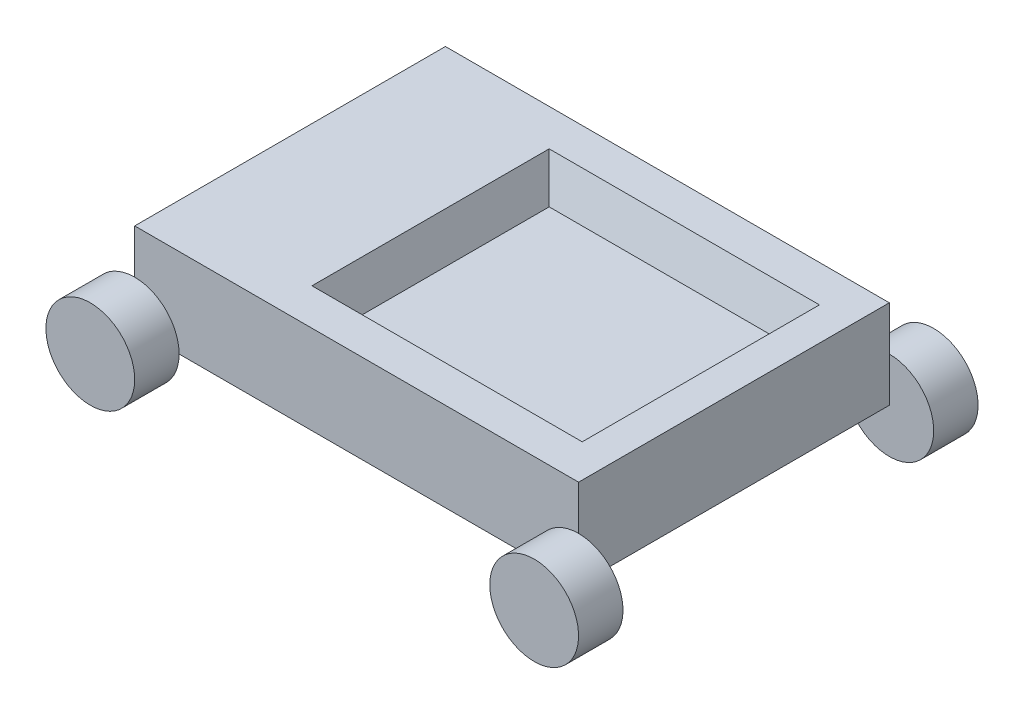
SolidWorks part; units mm, degrees
ref_plane "前视基准面" through (0, 0, 0) normal (0, 0, 1) x (1, 0, 0)
ref_plane "上视基准面" through (0, 0, 0) normal (0, 1, 0) x (1, 0, 0)
ref_plane "右视基准面" through (0, 0, 0) normal (1, 0, 0) x (0, 0, -1)
sketch "草图1" plane through (0, 0, 0) normal (0, 1, 0) x (1, 0, 0)
  line L1 (500, -350) -> (-500, -350)
  line L2 (500, -350) -> (500, 350)
  line L3 (500, 350) -> (-500, 350)
  line L4 (-500, -350) -> (-500, 350)
  line L5 (500, -350) -> (-500, 350) construction
  line L6 (500, 350) -> (-500, -350) construction
  point P0 (0, 0)
  dimension "D1" = 1000
  dimension "D2" = 700
extrude "凸台-拉伸1" add sketch "草图1" along normal blind 200
sketch "草图2" plane through (0, 0, 350) normal (0, 0, 1) x (1, 0, 0)
  circle A0 centre (-500, 0) radius 100
  dimension "D1" = 200
extrude "凸台-拉伸2" add sketch "草图2" along normal blind 100
mirror "镜向1" about plane through (0, 0, 0) normal (1, 0, 0) of "凸台-拉伸2"
mirror "镜向2" about plane through (0, 0, 0) normal (0, 0, 1) of "镜向1", "凸台-拉伸2"
sketch "草图3" plane through (0, 200, 0) normal (0, 1, 0) x (1, 0, 0)
  line L5 (-183.4427, -267.1882) -> (425.3743, -267.1882)
  line L6 (-183.4427, -267.1882) -> (-183.4427, 267.1882)
  line L7 (-183.4427, 267.1882) -> (425.3743, 267.1882)
  line L8 (425.3743, -267.1882) -> (425.3743, 267.1882)
  line L9 (-183.4427, -267.1882) -> (425.3743, 267.1882) construction
  line L10 (-183.4427, 267.1882) -> (425.3743, -267.1882) construction
  point P0 (0, 0)
  point P1 (120.9658, 0)
  point P6 (-128.9416, 0)
  point P8 (120.9658, 0)
extrude "切除-拉伸1" cut sketch "草图3" against normal blind 83 draft 20
